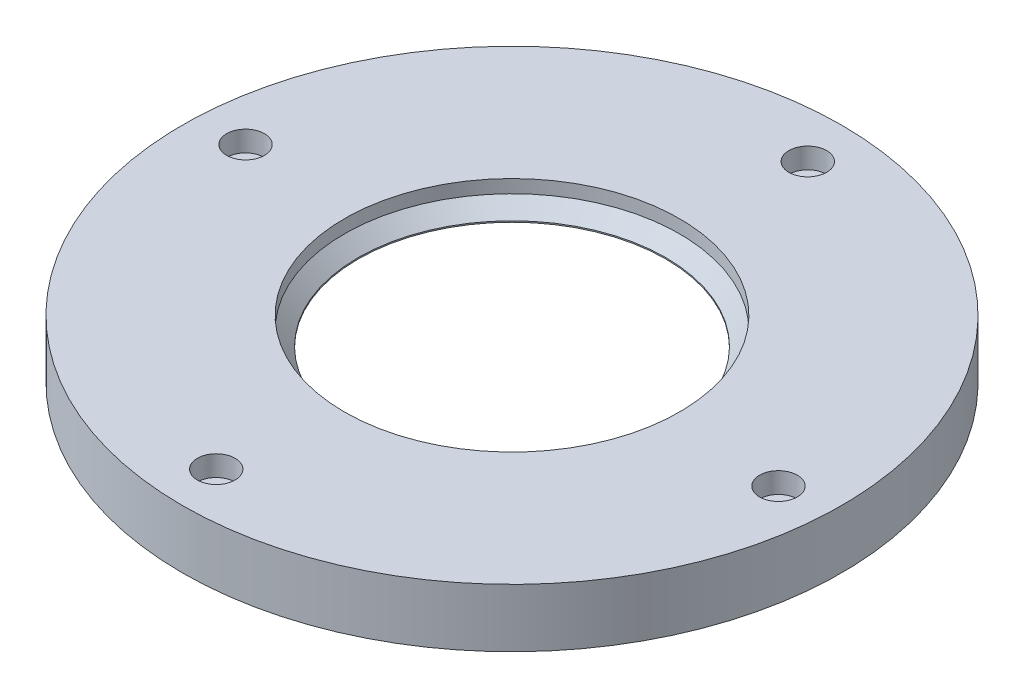
SolidWorks part; units mm, degrees
ref_plane "Front Plane" through (0, 0, 0) normal (0, 0, 1) x (1, 0, 0)
ref_plane "Top Plane" through (0, 0, 0) normal (0, 1, 0) x (1, 0, 0)
ref_plane "Right Plane" through (0, 0, 0) normal (1, 0, 0) x (0, 0, -1)
sketch "Sketch1" plane through (0, -49.0466, 0) normal (-0.0521, 0, 0.9986) x (0.9986, 0, 0.0521)
  line L0 (0, 13.8801) -> (0, -5.0159) construction
sketch "Sketch2" plane through (0, -49.0466, 0) normal (-0.0521, 0, 0.9986) x (0.9986, 0, 0.0521)
  line L0 (-25.6, 4.4) -> (-22.4, 4.4)
  line L1 (-22.4, 4.4) -> (-22.4, 4.5843)
  line L2 (-22.4, 4.5843) -> (-24.4, 6.5843)
  line L3 (-24.4, 6.5843) -> (-24.4, 8.5)
  line L4 (-24.4, 8.5) -> (-48, 8.5)
  line L5 (-48, 8.5) -> (-48, 0)
  line L6 (-48, 0) -> (-34, 0)
  line L7 (-34, 0) -> (-34, 2)
  line L8 (-34, 2) -> (-27.9, 2)
  line L9 (-27.9, 2) -> (-27.9, 7)
  line L10 (-27.9, 7) -> (-25.6, 7)
  line L11 (-25.6, 7) -> (-25.6, 4.4)
  line L12 (-24, 12) -> (-24, 6.75) construction
  line L13 (-22, 4.75) -> (-22, 4) construction
  line L14 (26, 4) -> (-26, 4) construction
  line L15 (-26, 6.6) -> (-26, 4) construction
  line L16 (27.5, 6.6) -> (-27.5, 6.6) construction
  line L17 (-27.5, 6.6) -> (-27.5, 2) construction
  line L18 (-27.5, 2) -> (27.5, 2) construction
  line L19 (-23.75, 0) -> (23.75, 0) construction
  line L22 (-24, 6.75) -> (-22, 4.75) construction
  line L23 (0, 200013.8801) -> (0, -200005.0159) construction
  point P9 (0, 0)
  point P30 (-26.4, 7)
  dimension "D1" = 0.4
  dimension "D2" = 0.4
  dimension "D3" = 0.4
  dimension "D4" = 0.4
  dimension "D5" = 0.4
  dimension "D6" = 0.4
  dimension "D7" = 8.5
  dimension "D8" = 0.4
  dimension "D9" = 48
  dimension "D10" = 34
revolve "Revolve1" add sketch "Sketch2" angle 360 about L0
fillet "Fillet1" radius 1 1 edges at (0, -47.0466, 34)
hole_wizard "CBORE for M2.5 SHCS1" positions "Sketch3" profile "Sketch4" counterbore size "M2.5" standard "ANSI Metric"
sketch "Sketch3" plane through (0, -40.5466, 0) normal (0, 1, 0) x (1, 0, 0)
  line L0 (-0.3437, -6.591) -> (0.3437, 6.591) construction
  line L1 (-6.591, 0.3437) -> (6.591, -0.3437) construction
  point P0 (2.1352, 40.9444)
  point P4 (40.9444, -2.1352)
  point P8 (-40.9444, 2.1352)
  point P10 (-2.1352, -40.9444)
  dimension "D1" = 82
  dimension "D2" = 82
  dimension "D3" = 41
  dimension "D4" = 41
sketch "Sketch4" plane through (2.1352, -40.5466, -40.9444) normal (1, 0, 0) x (0, 0, 1)
  line L0 (0, 0) -> (0, 10.8712)
  line L1 (0, 10.8712) -> (1.45, 10)
  line L2 (1.45, 10) -> (1.45, 3)
  line L3 (1.45, 3) -> (2.75, 3)
  line L4 (2.75, 3) -> (2.75, 0)
  line L5 (2.75, 0) -> (0, 0)
  line L10 (0, 10.8712) -> (-1.45, 10) construction
  line L11 (0, -6.35) -> (0, 107.95) construction
  dimension "Hole Dia." = 2.9
  dimension "Hole Depth" = 10
  dimension "C'Bore Dia." = 5.5
  dimension "C'Bore Depth" = 3
  dimension "Drill Angle" = 118
